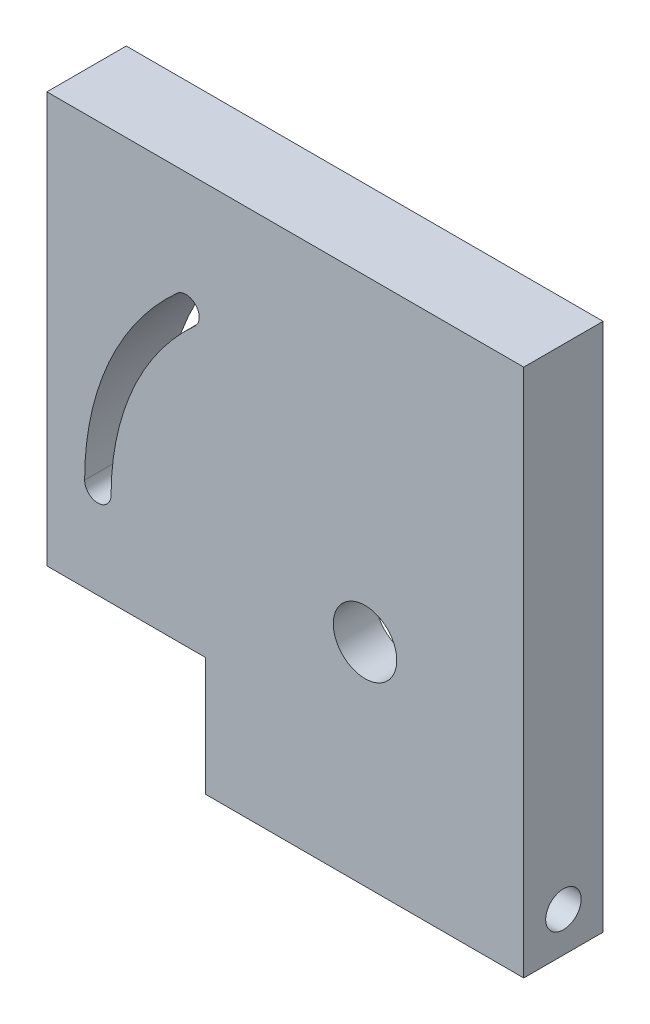
SolidWorks part; units mm, degrees
ref_plane "Спереди" through (0, 0, 0) normal (0, 0, 1) x (1, 0, 0)
ref_plane "Сверху" through (0, 0, 0) normal (0, 1, 0) x (1, 0, 0)
ref_plane "Справа" through (0, 0, 0) normal (1, 0, 0) x (0, 0, -1)
ref_plane "Плоскость1" through (0, 0, 15) normal (0, 0, 1) x (1, 0, 0)
sketch "Эскиз1" plane through (0, 0, 15) normal (0, 0, 1) x (1, 0, 0)
  line L0 (-60.1334, -40) -> (30, -40)
  line L1 (30, -40) -> (30, 60)
  line L2 (30, 60) -> (-60.1334, 60)
  line L3 (-60.1334, 60) -> (-60.1334, -40)
extrude "Бобышка-Вытянуть1" add sketch "Эскиз1" against normal blind 15
hole_wizard "Цековка для  болта с шестигранной головкой M101" positions "Эскиз7" profile "Эскиз6" counterbore size "M10" standard "Ansi Metric"
sketch "Эскиз7" plane through (0, 0, 0) normal (0, 0, -1) x (-1, 0, 0)
  point P0 (0, 0)
sketch "Эскиз6" plane through (0, 0, 0) normal (1, 0, 0) x (0, 1, 0)
  line L0 (0, 0) -> (0, 15)
  line L1 (0, 15) -> (6, 15)
  line L3 (6, 15) -> (6, 7)
  line L4 (6, 7) -> (17.5, 7)
  line L5 (17.5, 7) -> (17.5, 0)
  line L7 (17.5, 0) -> (0, 0)
  line L11 (0, -6.35) -> (0, 107.95) construction
  dimension "Диаметр сквозного отверстия" = 12
  dimension "Глубина сквозного отверстия" = 15
  dimension "Диаметр цековки" = 35
  dimension "Глубина цековки" = 7
sketch "Эскиз10" plane through (-60.1334, 0, 0) normal (-1, 0, 0) x (0, 0, 1)
  line L0 (15, 60) -> (15, -40) construction
  line L1 (0, -40) -> (15, -40)
  line L2 (0, -40) -> (0, -17.6109)
  line L3 (0, -17.6109) -> (15, -17.6109)
  line L4 (15, -40) -> (15, -17.6109)
extrude "Вырез-Вытянуть3" cut sketch "Эскиз10" against normal blind 30
sketch "Эскиз12" plane through (-30.1334, 0, 0) normal (-1, 0, 0) x (0, 0, 1)
  line L1 (0, -40) -> (15, -40)
  line L2 (0, -40) -> (0, -25)
  line L3 (0, -25) -> (15, -25)
  line L4 (15, -40) -> (15, -25)
  circle A0 centre (7.5, -32.5) radius 3.35
extrude "Вырез-Вытянуть4" cut sketch "Эскиз12" against normal blind 10 contours A0
sketch "Эскиз14" plane through (30, 0, 0) normal (1, 0, 0) x (0, 0, -1)
  line L0 (0, -40) -> (0, 60) construction
  line L1 (-15, -40) -> (0, -40)
  line L2 (-15, -40) -> (-15, -25)
  line L3 (-15, -25) -> (0, -25)
  line L4 (0, -40) -> (0, -25)
  line L5 (-15, -40) -> (0, -25)
  line L6 (0, -40) -> (-15, -25)
  line L7 (-16.5518, -32.5) -> (1.7105, -32.5) construction
  circle A0 centre (-7.5, -32.5) radius 3.35
extrude "Вырез-Вытянуть5" cut sketch "Эскиз14" against normal blind 10 contours A0
sketch "Эскиз18" plane through (0, 0, 15) normal (0, 0, 1) x (1, 0, 0)
  arc A1 (-50.5033, 0) -> (-33.8492, 37.4809) centre (0, 0) cw construction
  arc A2 (-35.5248, 39.3362) -> (-53.0033, 0) centre (0, 0) ccw
  arc A3 (-32.1736, 35.6255) -> (-48.0033, 0) centre (0, 0) ccw
  arc A4 (-32.1736, 35.6255) -> (-35.5248, 39.3362) centre (-33.8492, 37.4809) ccw
  arc A5 (-53.0033, 0) -> (-48.0033, 0) centre (-50.5033, 0) ccw
  point P6 (-46.1524, 20.5071)
extrude "Вырез-Вытянуть6" cut sketch "Эскиз18" against normal through all
